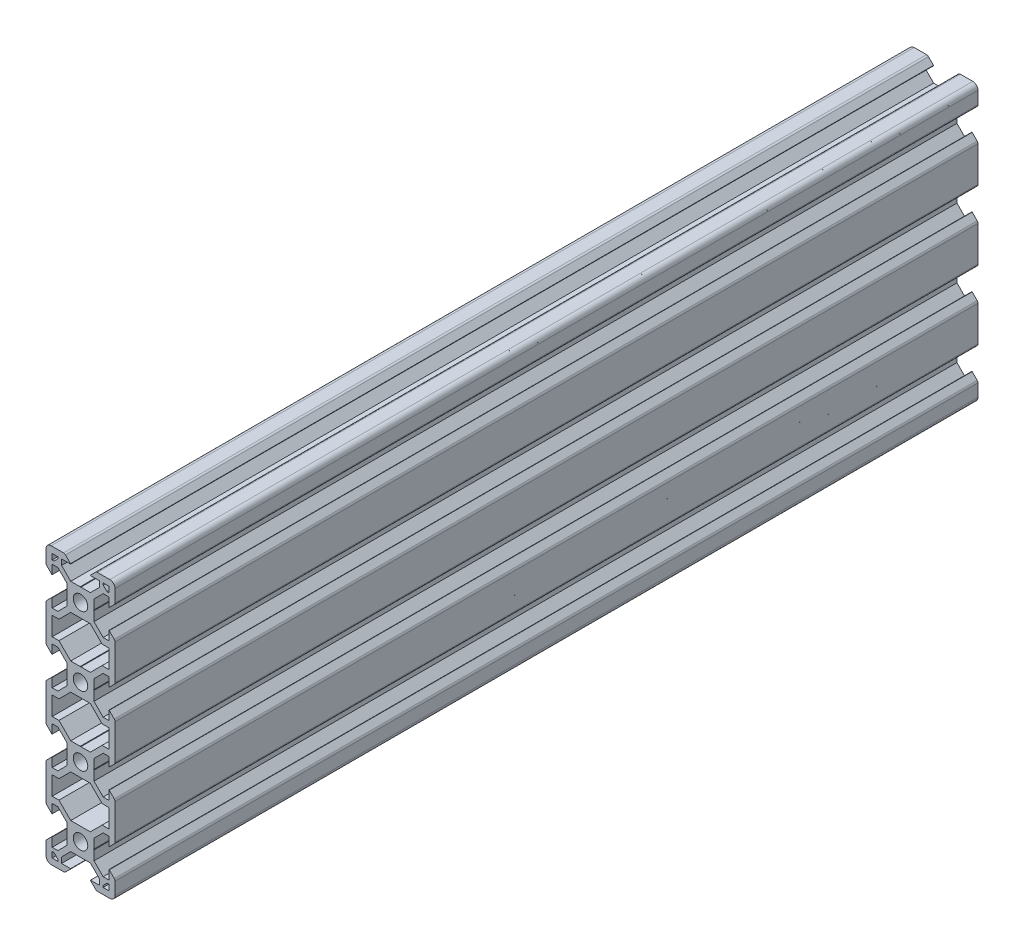
SolidWorks part; units mm, degrees
ref_plane "Front Plane" through (0, 0, 0) normal (0, 0, 1) x (1, 0, 0)
ref_plane "Top Plane" through (0, 0, 0) normal (0, 1, 0) x (1, 0, 0)
ref_plane "Right Plane" through (0, 0, 0) normal (1, 0, 0) x (0, 0, -1)
sketch "Sketch2" plane through (0, 0, 0) normal (0, 0, 1) x (1, 0, 0)
  line L0 (-8.2, 2.8875) -> (-8.2, 5.4975)
  line L3 (-4.9072, 9.9975) -> (-8.5, 9.9975)
  line L4 (-10, 4.9047) -> (-10, 8.4975)
  line L5 (-2.1, 0) -> (-3.8, 0) construction
  line L6 (0, 3.8) -> (0, 2.1) construction
  line L7 (-0.1, 3.9) -> (-2.8404, 3.9)
  line L8 (-3.9, 0.1) -> (-3.9, 2.8383)
  line L9 (-2.89, 8.1975) -> (-5.5, 8.1975)
  line L10 (-6.57, 8.1975) -> (-6.57, 7.6575)
  line L11 (-8.2, 6.5675) -> (-7.66, 6.5675)
  line L12 (-5.5, 8.1975) -> (-5.5, 6.5588)
  line L13 (-6.56, 5.4975) -> (-8.2, 5.4975)
  line L14 (-8.2, 8.1975) -> (-1.4852, 1.4847) construction
  line L15 (-6.56, 5.4975) -> (-3.9, 2.8383)
  line L16 (-5.5, 6.5588) -> (-2.8404, 3.9)
  line L17 (-7.66, 6.5675) -> (-6.57, 7.6575)
  line L18 (-8.7302, 7.6671) -> (-0.5302, -0.5304) construction
  line L19 (-7.6698, 8.7279) -> (0.5302, 0.5304) construction
  line L20 (-8.2, 8.1975) -> (0, 0) construction
  line L21 (-8.2, 6.5675) -> (-8.2, 8.1975)
  line L22 (-8.2, -0.0025) -> (-8.2, 8.1975) construction
  line L23 (-6.57, 8.1975) -> (-8.2, 8.1975)
  line L24 (0, 8.1975) -> (-8.2, 8.1975) construction
  line L25 (-10, -0.0025) -> (-10, 9.9975) construction
  line L26 (0, 9.9975) -> (-10, 9.9975) construction
  line L27 (-2.89, 8.3075) -> (-2.89, 8.1975)
  line L29 (-8.31, 2.8875) -> (-8.2, 2.8875)
  line L30 (-4.3486, 9.7661) -> (-2.89, 8.3075)
  line L31 (-8.31, 2.8875) -> (-9.7686, 4.3461)
  line L34 (-0.1, 3.9) -> (0, 3.8)
  line L35 (-3.9, 0.1) -> (-3.8, 0)
  line L36 (-10, -20) -> (0, -20) construction
  line L37 (0, 0) -> (0, -20) construction
  line L38 (0, -3.9) -> (-2.8404, -3.9)
  line L39 (-3.8, 0) -> (-3.9, -0.1)
  line L40 (-3.9, -0.1) -> (-3.9, -2.84)
  line L41 (-2.8404, -3.9) -> (-6.25, -7.3096)
  line L42 (-3.9, -2.84) -> (-6.56, -5.5)
  line L43 (-8.21, -2.89) -> (-8.21, -5.5)
  line L44 (-6.56, 5.4975) -> (-6.56, -5.5) construction
  line L45 (-6.56, -5.5) -> (-8.21, -5.5)
  line L46 (-6.25, -7.3096) -> (-6.25, -12.7) construction
  line L47 (-6.25, -7.3096) -> (-8.21, -7.3096)
  line L48 (-8.21, -2.89) -> (-8.31, -2.89)
  line L49 (-8.31, -2.89) -> (-9.7657, -4.3457)
  line L51 (-8.21, -7.3096) -> (-8.21, -12.7)
  line L52 (-0.1, -16.1) -> (-2.85, -16.1)
  line L53 (-3.9, -17.16) -> (-3.9, -19.9)
  line L54 (-6.25, -12.7) -> (-2.85, -16.1)
  line L58 (-3.9, -17.16) -> (-6.56, -14.5)
  line L60 (-8.21, -17.11) -> (-8.31, -17.11)
  line L61 (-10, -4.9114) -> (-10, -15.0886)
  line L62 (-9.7657, -15.6543) -> (-8.31, -17.11)
  line L63 (-0.1, -16.1) -> (0, -16.2)
  line L64 (-3.9, -19.9) -> (-3.8, -20)
  line L65 (-8.21, -14.5) -> (-6.56, -14.5)
  line L66 (-8.21, -12.7) -> (-6.25, -12.7)
  line L67 (-10, -30.01) -> (0, -30.01) construction
  line L68 (-8.21, -14.5) -> (-8.21, -17.11)
  line L69 (-3.9, -20.1) -> (-3.8, -20)
  line L71 (-10, -20) -> (0, -20) construction
  line L72 (-8.21, -30.01) -> (-8.21, -27.31)
  line L73 (-10, -30.01) -> (-10, -24.9101)
  line L74 (-8.21, -25.4987) -> (-8.21, -22.8887)
  line L76 (-8.21, -27.31) -> (-6.25, -27.31)
  line L77 (-8.21, -25.4987) -> (-6.56, -25.4987)
  line L85 (-0.1, -23.9) -> (0, -23.8)
  line L95 (-9.7657, -24.3444) -> (-8.31, -22.8887)
  line L96 (-8.21, -22.8887) -> (-8.31, -22.8887)
  line L97 (-3.9, -22.8387) -> (-6.56, -25.4987)
  line L98 (-6.25, -27.31) -> (-2.84, -23.9)
  line L99 (-3.9, -22.8387) -> (-3.9, -20.1)
  line L100 (-0.1, -23.9) -> (-2.84, -23.9)
  arc A1 (-10, 8.4975) -> (-8.5, 9.9975) centre (-8.5, 8.4975) cw
  arc A2 (-9.7686, 4.3461) -> (-10, 4.9047) centre (-9.21, 4.9047) cw
  arc A3 (-4.3486, 9.7661) -> (-4.9072, 9.9975) centre (-4.9072, 9.2075) ccw
  arc A5 (0, 2.1) -> (0, -2.1) centre (0, 0) ccw
  arc A6 (-9.7657, -15.6543) -> (-10, -15.0886) centre (-9.2, -15.0886) cw
  arc A7 (-9.7657, -4.3457) -> (-10, -4.9114) centre (-9.2, -4.9114) ccw
  arc A8 (0, -17.9) -> (0, -22.1) centre (0, -20) ccw
  arc A10 (-9.7657, -24.3444) -> (-10, -24.9101) centre (-9.2, -24.9101) ccw
  point P29 (-10, 9.9975)
  point P39 (-10, 4.5775)
  point P42 (-4.58, 9.9975)
  point P76 (-10, -15.42)
  point P79 (-10, -4.58)
  dimension "D15" = 1.5
  dimension "D22" = 0.79
  dimension "D30" = 2.1
  dimension "D31" = 2.1
  dimension "D51" = 0.8
  dimension "D52" = 2.61
  dimension "D64" = 1.65
  dimension "D53" = 0.8
  dimension "D55" = 3.9
  dimension "D4" = 1.8
  dimension "D5" = 3.43
  dimension "D6" = 3.43
  dimension "D7" = 0.54
  dimension "D8" = 0.54
  dimension "D9" = 1.07
  dimension "D10" = 1.07
  dimension "D11" = 3.9
  dimension "D12" = 3.9
  dimension "D16" = 7.11
  dimension "D17" = 0.11
  dimension "D18" = 1.69
  dimension "D19" = 0.11
  dimension "D20" = 7.11
  dimension "D21" = 1.69
  dimension "D23" = 10
  dimension "D24" = 0.1
  dimension "D25" = 45
  dimension "D26" = 0.1
  dimension "D27" = 45
  dimension "D28" = 1.64
  dimension "D29" = 20
  dimension "D32" = 3.9
  dimension "D33" = 45
  dimension "D34" = 2.74
  dimension "D35" = 45
  dimension "D36" = 1.96
  dimension "D37" = 2.61
  dimension "D38" = 90
  dimension "D39" = 2.61
  dimension "D40" = 3.9
  dimension "D41" = 3.9
  dimension "D42" = 135
  dimension "D44" = 45
  dimension "D45" = 1.8
  dimension "D46" = 0.1
  dimension "D47" = 0.1
  dimension "D48" = 45
  dimension "D49" = 0.1
  dimension "D50" = 45
  dimension "D43" = 5.5
  dimension "D54" = 3.9
  dimension "D56" = 45
  dimension "D57" = 2.7
  dimension "D59" = 45
  dimension "D60" = 0.1
  dimension "D61" = 0.1
  dimension "D62" = 45
  dimension "D63" = 2.84
  dimension "D65" = 1.96
  dimension "D66" = 45
  dimension "D67" = 1.5
  dimension "D13" = 0.75
  dimension "D14" = 0.75
sketch "Sketch3" plane through (0, 0, 0) normal (0, 0, 1) x (1, 0, 0)
  line L0 (-0.1, 3.9) -> (0, 3.8) construction
  line L1 (-0.1, 3.9) -> (-2.8404, 3.9) construction
  line L2 (-5.5, 6.5588) -> (-2.8404, 3.9) construction
  line L3 (-5.5, 8.1975) -> (-5.5, 6.5588) construction
  line L4 (-2.89, 8.1975) -> (-5.5, 8.1975) construction
  line L5 (-7.66, 6.5675) -> (-6.57, 7.6575)
  line L6 (-6.57, 7.6575) -> (-6.57, 8.1975)
  line L7 (-6.57, 8.1975) -> (-8.2, 8.1975)
  line L8 (-8.2, 8.1975) -> (-8.2, 6.5675)
  line L9 (-8.2, 6.5675) -> (-7.66, 6.5675)
  line L10 (-7.66, 6.5675) -> (-6.57, 7.6575)
  line L11 (-6.57, 7.6575) -> (-6.57, 8.1975)
  line L12 (-6.57, 8.1975) -> (-8.2, 8.1975)
  line L13 (-8.2, 8.1975) -> (-8.2, 6.5675)
  line L14 (-8.2, 6.5675) -> (-7.66, 6.5675)
  line L15 (-2.89, 8.3075) -> (-2.89, 8.1975) construction
  line L16 (-4.3486, 9.7661) -> (-2.89, 8.3075) construction
  line L17 (-4.9072, 9.9975) -> (-8.5, 9.9975) construction
  line L18 (-10, 4.9047) -> (-10, 8.4975) construction
  line L19 (-8.31, 2.8875) -> (-9.7686, 4.3461) construction
  line L20 (-8.31, 2.8875) -> (-8.2, 2.8875) construction
  line L21 (-8.2, 2.8875) -> (-8.2, 5.4975) construction
  line L22 (-6.56, 5.4975) -> (-8.2, 5.4975) construction
  line L23 (-6.56, 5.4975) -> (-3.9, 2.8383) construction
  line L24 (-3.9, 0.1) -> (-3.9, 2.8383) construction
  line L25 (-3.9, 0.1) -> (-3.8, 0) construction
  line L26 (-3.8, 0) -> (-3.9, -0.1) construction
  line L27 (-3.9, -0.1) -> (-3.9, -2.84) construction
  line L28 (-3.9, -2.84) -> (-6.56, -5.5) construction
  line L29 (-6.56, -5.5) -> (-8.21, -5.5) construction
  line L30 (-8.21, -2.89) -> (-8.21, -5.5) construction
  line L31 (-8.21, -2.89) -> (-8.31, -2.89) construction
  line L32 (-8.31, -2.89) -> (-9.7657, -4.3457) construction
  line L33 (-10, -4.9114) -> (-10, -15.0886) construction
  line L34 (-9.7657, -15.6543) -> (-8.31, -17.11) construction
  line L35 (-8.21, -17.11) -> (-8.31, -17.11) construction
  line L36 (-8.21, -14.5) -> (-8.21, -17.11) construction
  line L37 (-8.21, -14.5) -> (-6.56, -14.5) construction
  line L38 (-3.9, -17.16) -> (-6.56, -14.5) construction
  line L39 (-3.9, -17.16) -> (-3.9, -19.9) construction
  line L40 (-3.9, -19.9) -> (-3.8, -20) construction
  line L41 (-3.9, -20.1) -> (-3.8, -20) construction
  line L42 (-3.9, -22.8387) -> (-3.9, -20.1) construction
  line L43 (-3.9, -22.8387) -> (-6.56, -25.4987) construction
  line L44 (-8.21, -25.4987) -> (-6.56, -25.4987) construction
  line L45 (-8.21, -25.4987) -> (-8.21, -22.8887) construction
  line L46 (-8.21, -22.8887) -> (-8.31, -22.8887) construction
  line L47 (-9.7657, -24.3444) -> (-8.31, -22.8887) construction
  line L48 (-10, -30.01) -> (-10, -24.9101) construction
  line L49 (0, -3.9) -> (-2.8404, -3.9) construction
  line L50 (-2.8404, -3.9) -> (-6.25, -7.3096) construction
  line L51 (-6.25, -7.3096) -> (-8.21, -7.3096) construction
  line L52 (-8.21, -7.3096) -> (-8.21, -12.7) construction
  line L53 (-8.21, -12.7) -> (-6.25, -12.7) construction
  line L54 (-6.25, -12.7) -> (-2.85, -16.1) construction
  line L55 (-0.1, -16.1) -> (-2.85, -16.1) construction
  line L56 (-0.1, -16.1) -> (0, -16.2) construction
  line L57 (-0.1, -23.9) -> (0, -23.8) construction
  line L58 (-0.1, -23.9) -> (-2.84, -23.9) construction
  line L59 (-6.25, -27.31) -> (-2.84, -23.9) construction
  line L60 (-8.21, -27.31) -> (-6.25, -27.31) construction
  line L61 (-8.21, -30.01) -> (-8.21, -27.31) construction
  line L62 (-0.1, 3.9) -> (0, 3.8)
  line L63 (-0.1, 3.9) -> (-2.8404, 3.9)
  line L64 (-5.5, 6.5588) -> (-2.8404, 3.9)
  line L65 (-5.5, 8.1975) -> (-5.5, 6.5588)
  line L66 (-2.89, 8.1975) -> (-5.5, 8.1975)
  line L67 (-2.89, 8.3075) -> (-2.89, 8.1975)
  line L68 (-4.3486, 9.7661) -> (-2.89, 8.3075)
  line L69 (-4.9072, 9.9975) -> (-8.5, 9.9975)
  line L70 (-10, 4.9047) -> (-10, 8.4975)
  line L71 (-8.31, 2.8875) -> (-9.7686, 4.3461)
  line L72 (-8.31, 2.8875) -> (-8.2, 2.8875)
  line L73 (-8.2, 2.8875) -> (-8.2, 5.4975)
  line L74 (-6.56, 5.4975) -> (-8.2, 5.4975)
  line L75 (-6.56, 5.4975) -> (-3.9, 2.8383)
  line L76 (-3.9, 0.1) -> (-3.9, 2.8383)
  line L77 (-3.9, 0.1) -> (-3.8, 0)
  line L78 (-3.8, 0) -> (-3.9, -0.1)
  line L79 (-3.9, -0.1) -> (-3.9, -2.84)
  line L80 (-3.9, -2.84) -> (-6.56, -5.5)
  line L81 (-6.56, -5.5) -> (-8.21, -5.5)
  line L82 (-8.21, -2.89) -> (-8.21, -5.5)
  line L83 (-8.21, -2.89) -> (-8.31, -2.89)
  line L84 (-8.31, -2.89) -> (-9.7657, -4.3457)
  line L85 (-10, -4.9114) -> (-10, -15.0886)
  line L86 (-9.7657, -15.6543) -> (-8.31, -17.11)
  line L87 (-8.21, -17.11) -> (-8.31, -17.11)
  line L88 (-8.21, -14.5) -> (-8.21, -17.11)
  line L89 (-8.21, -14.5) -> (-6.56, -14.5)
  line L90 (-3.9, -17.16) -> (-6.56, -14.5)
  line L91 (-3.9, -17.16) -> (-3.9, -19.9)
  line L92 (-3.9, -19.9) -> (-3.8, -20)
  line L93 (-3.9, -20.1) -> (-3.8, -20)
  line L94 (-3.9, -22.8387) -> (-3.9, -20.1)
  line L95 (-3.9, -22.8387) -> (-6.56, -25.4987)
  line L96 (-8.21, -25.4987) -> (-6.56, -25.4987)
  line L97 (-8.21, -25.4987) -> (-8.21, -22.8887)
  line L98 (-8.21, -22.8887) -> (-8.31, -22.8887)
  line L99 (-9.7657, -24.3444) -> (-8.31, -22.8887)
  line L100 (-10, -35.1099) -> (-10, -24.9101)
  line L101 (2.8404, -3.9) -> (-2.8404, -3.9)
  line L102 (-2.8404, -3.9) -> (-6.25, -7.3096)
  line L103 (-6.25, -7.3096) -> (-8.21, -7.3096)
  line L104 (-8.21, -7.3096) -> (-8.21, -12.7)
  line L105 (-8.21, -12.7) -> (-6.25, -12.7)
  line L106 (-6.25, -12.7) -> (-2.85, -16.1)
  line L107 (-0.1, -16.1) -> (-2.85, -16.1)
  line L108 (-0.1, -16.1) -> (0, -16.2)
  line L109 (-0.1, -23.9) -> (0, -23.8)
  line L110 (-0.1, -23.9) -> (-2.84, -23.9)
  line L111 (-6.25, -27.31) -> (-2.84, -23.9)
  line L112 (-8.21, -27.31) -> (-6.25, -27.31)
  line L113 (-8.21, -32.71) -> (-8.21, -27.31)
  line L114 (0, 0) -> (0, -20) construction
  line L115 (-10, -30.01) -> (0, -30.01) construction
  line L116 (0, 0) -> (0, -20) construction
  line L117 (-10, -30.01) -> (10, -30.01) construction
  line L118 (8.21, -32.71) -> (8.21, -27.31)
  line L119 (8.21, -27.31) -> (6.25, -27.31)
  line L120 (6.25, -27.31) -> (2.84, -23.9)
  line L121 (0.1, -23.9) -> (2.84, -23.9)
  line L122 (0.1, -23.9) -> (0, -23.8)
  line L123 (0.1, -16.1) -> (0, -16.2)
  line L124 (0.1, -16.1) -> (2.85, -16.1)
  line L125 (6.25, -12.7) -> (2.85, -16.1)
  line L126 (8.21, -12.7) -> (6.25, -12.7)
  line L127 (8.21, -7.3096) -> (8.21, -12.7)
  line L128 (6.25, -7.3096) -> (8.21, -7.3096)
  line L129 (2.8404, -3.9) -> (6.25, -7.3096)
  line L130 (10, -35.1099) -> (10, -24.9101)
  line L131 (9.7657, -24.3444) -> (8.31, -22.8887)
  line L132 (8.21, -22.8887) -> (8.31, -22.8887)
  line L133 (8.21, -25.4987) -> (8.21, -22.8887)
  line L134 (8.21, -25.4987) -> (6.56, -25.4987)
  line L135 (3.9, -22.8387) -> (6.56, -25.4987)
  line L136 (3.9, -22.8387) -> (3.9, -20.1)
  line L137 (3.9, -20.1) -> (3.8, -20)
  line L138 (3.9, -19.9) -> (3.8, -20)
  line L139 (3.9, -17.16) -> (3.9, -19.9)
  line L140 (3.9, -17.16) -> (6.56, -14.5)
  line L141 (8.21, -14.5) -> (6.56, -14.5)
  line L142 (8.21, -14.5) -> (8.21, -17.11)
  line L143 (8.21, -17.11) -> (8.31, -17.11)
  line L144 (9.7657, -15.6543) -> (8.31, -17.11)
  line L145 (10, -4.9114) -> (10, -15.0886)
  line L146 (8.31, -2.89) -> (9.7657, -4.3457)
  line L147 (8.21, -2.89) -> (8.31, -2.89)
  line L148 (8.21, -2.89) -> (8.21, -5.5)
  line L149 (6.56, -5.5) -> (8.21, -5.5)
  line L150 (3.9, -2.84) -> (6.56, -5.5)
  line L151 (3.9, -0.1) -> (3.9, -2.84)
  line L152 (3.8, 0) -> (3.9, -0.1)
  line L153 (3.9, 0.1) -> (3.8, 0)
  line L154 (3.9, 0.1) -> (3.9, 2.8383)
  line L155 (6.56, 5.4975) -> (3.9, 2.8383)
  line L156 (6.56, 5.4975) -> (8.2, 5.4975)
  line L157 (8.2, 2.8875) -> (8.2, 5.4975)
  line L158 (8.31, 2.8875) -> (8.2, 2.8875)
  line L159 (8.31, 2.8875) -> (9.7686, 4.3461)
  line L160 (10, 4.9047) -> (10, 8.4975)
  line L161 (4.9072, 9.9975) -> (8.5, 9.9975)
  line L162 (4.3486, 9.7661) -> (2.89, 8.3075)
  line L163 (2.89, 8.3075) -> (2.89, 8.1975)
  line L164 (2.89, 8.1975) -> (5.5, 8.1975)
  line L165 (5.5, 8.1975) -> (5.5, 6.5588)
  line L166 (5.5, 6.5588) -> (2.8404, 3.9)
  line L167 (0.1, 3.9) -> (2.8404, 3.9)
  line L168 (0.1, 3.9) -> (0, 3.8)
  line L169 (8.2, 6.5675) -> (7.66, 6.5675)
  line L170 (8.2, 8.1975) -> (8.2, 6.5675)
  line L171 (6.57, 8.1975) -> (8.2, 8.1975)
  line L172 (6.57, 7.6575) -> (6.57, 8.1975)
  line L173 (7.66, 6.5675) -> (6.57, 7.6575)
  line L174 (0, -60.02) -> (0, -40.02) construction
  line L175 (7.66, -66.5875) -> (6.57, -67.6775)
  line L176 (6.57, -67.6775) -> (6.57, -68.2175)
  line L177 (6.57, -68.2175) -> (8.2, -68.2175)
  line L178 (8.2, -68.2175) -> (8.2, -66.5875)
  line L179 (8.2, -66.5875) -> (7.66, -66.5875)
  line L180 (0.1, -63.92) -> (0, -63.82)
  line L181 (0.1, -63.92) -> (2.8404, -63.92)
  line L182 (5.5, -66.5788) -> (2.8404, -63.92)
  line L183 (5.5, -68.2175) -> (5.5, -66.5788)
  line L184 (2.89, -68.2175) -> (5.5, -68.2175)
  line L185 (2.89, -68.3275) -> (2.89, -68.2175)
  line L186 (4.3486, -69.7861) -> (2.89, -68.3275)
  line L187 (4.9072, -70.0175) -> (8.5, -70.0175)
  line L188 (10, -64.9247) -> (10, -68.5175)
  line L189 (8.31, -62.9075) -> (9.7686, -64.3661)
  line L190 (8.31, -62.9075) -> (8.2, -62.9075)
  line L191 (8.2, -62.9075) -> (8.2, -65.5175)
  line L192 (6.56, -65.5175) -> (8.2, -65.5175)
  line L193 (6.56, -65.5175) -> (3.9, -62.8583)
  line L194 (3.9, -60.12) -> (3.9, -62.8583)
  line L195 (3.9, -60.12) -> (3.8, -60.02)
  line L196 (3.8, -60.02) -> (3.9, -59.92)
  line L197 (3.9, -59.92) -> (3.9, -57.18)
  line L198 (3.9, -57.18) -> (6.56, -54.52)
  line L199 (6.56, -54.52) -> (8.21, -54.52)
  line L200 (8.21, -57.13) -> (8.21, -54.52)
  line L201 (8.21, -57.13) -> (8.31, -57.13)
  line L202 (8.31, -57.13) -> (9.7657, -55.6743)
  line L203 (10, -55.1086) -> (10, -44.9314)
  line L204 (9.7657, -44.3657) -> (8.31, -42.91)
  line L205 (8.21, -42.91) -> (8.31, -42.91)
  line L206 (8.21, -45.52) -> (8.21, -42.91)
  line L207 (8.21, -45.52) -> (6.56, -45.52)
  line L208 (3.9, -42.86) -> (6.56, -45.52)
  line L209 (3.9, -42.86) -> (3.9, -40.12)
  line L210 (3.9, -40.12) -> (3.8, -40.02)
  line L211 (3.9, -39.92) -> (3.8, -40.02)
  line L212 (3.9, -37.1813) -> (3.9, -39.92)
  line L213 (3.9, -37.1813) -> (6.56, -34.5213)
  line L214 (8.21, -34.5213) -> (6.56, -34.5213)
  line L215 (8.21, -34.5213) -> (8.21, -37.1313)
  line L216 (8.21, -37.1313) -> (8.31, -37.1313)
  line L217 (9.7657, -35.6756) -> (8.31, -37.1313)
  line L218 (2.8404, -56.12) -> (6.25, -52.7104)
  line L219 (6.25, -52.7104) -> (8.21, -52.7104)
  line L220 (8.21, -52.7104) -> (8.21, -47.32)
  line L221 (8.21, -47.32) -> (6.25, -47.32)
  line L222 (6.25, -47.32) -> (2.85, -43.92)
  line L223 (0.1, -43.92) -> (2.85, -43.92)
  line L224 (0.1, -43.92) -> (0, -43.82)
  line L225 (0.1, -36.12) -> (0, -36.22)
  line L226 (0.1, -36.12) -> (2.84, -36.12)
  line L227 (6.25, -32.71) -> (2.84, -36.12)
  line L228 (8.21, -32.71) -> (6.25, -32.71)
  line L229 (-8.21, -32.71) -> (-6.25, -32.71)
  line L230 (-6.25, -32.71) -> (-2.84, -36.12)
  line L231 (-0.1, -36.12) -> (-2.84, -36.12)
  line L232 (-0.1, -36.12) -> (0, -36.22)
  line L233 (-0.1, -43.92) -> (0, -43.82)
  line L234 (-0.1, -43.92) -> (-2.85, -43.92)
  line L235 (-6.25, -47.32) -> (-2.85, -43.92)
  line L236 (-8.21, -47.32) -> (-6.25, -47.32)
  line L237 (-8.21, -52.7104) -> (-8.21, -47.32)
  line L238 (-6.25, -52.7104) -> (-8.21, -52.7104)
  line L239 (-2.8404, -56.12) -> (-6.25, -52.7104)
  line L240 (2.8404, -56.12) -> (-2.8404, -56.12)
  line L241 (-9.7657, -35.6756) -> (-8.31, -37.1313)
  line L242 (-8.21, -37.1313) -> (-8.31, -37.1313)
  line L243 (-8.21, -34.5213) -> (-8.21, -37.1313)
  line L244 (-8.21, -34.5213) -> (-6.56, -34.5213)
  line L245 (-3.9, -37.1813) -> (-6.56, -34.5213)
  line L246 (-3.9, -37.1813) -> (-3.9, -39.92)
  line L247 (-3.9, -39.92) -> (-3.8, -40.02)
  line L248 (-3.9, -40.12) -> (-3.8, -40.02)
  line L249 (-3.9, -42.86) -> (-3.9, -40.12)
  line L250 (-3.9, -42.86) -> (-6.56, -45.52)
  line L251 (-8.21, -45.52) -> (-6.56, -45.52)
  line L252 (-8.21, -45.52) -> (-8.21, -42.91)
  line L253 (-8.21, -42.91) -> (-8.31, -42.91)
  line L254 (-9.7657, -44.3657) -> (-8.31, -42.91)
  line L255 (-10, -55.1086) -> (-10, -44.9314)
  line L256 (-8.31, -57.13) -> (-9.7657, -55.6743)
  line L257 (-8.21, -57.13) -> (-8.31, -57.13)
  line L258 (-8.21, -57.13) -> (-8.21, -54.52)
  line L259 (-6.56, -54.52) -> (-8.21, -54.52)
  line L260 (-3.9, -57.18) -> (-6.56, -54.52)
  line L261 (-3.9, -59.92) -> (-3.9, -57.18)
  line L262 (-3.8, -60.02) -> (-3.9, -59.92)
  line L263 (-3.9, -60.12) -> (-3.8, -60.02)
  line L264 (-3.9, -60.12) -> (-3.9, -62.8583)
  line L265 (-6.56, -65.5175) -> (-3.9, -62.8583)
  line L266 (-6.56, -65.5175) -> (-8.2, -65.5175)
  line L267 (-8.2, -62.9075) -> (-8.2, -65.5175)
  line L268 (-8.31, -62.9075) -> (-8.2, -62.9075)
  line L269 (-8.31, -62.9075) -> (-9.7686, -64.3661)
  line L270 (-10, -64.9247) -> (-10, -68.5175)
  line L271 (-4.9072, -70.0175) -> (-8.5, -70.0175)
  line L272 (-4.3486, -69.7861) -> (-2.89, -68.3275)
  line L273 (-2.89, -68.3275) -> (-2.89, -68.2175)
  line L274 (-2.89, -68.2175) -> (-5.5, -68.2175)
  line L275 (-5.5, -68.2175) -> (-5.5, -66.5788)
  line L276 (-5.5, -66.5788) -> (-2.8404, -63.92)
  line L277 (-0.1, -63.92) -> (-2.8404, -63.92)
  line L278 (-0.1, -63.92) -> (0, -63.82)
  line L279 (-8.2, -66.5875) -> (-7.66, -66.5875)
  line L280 (-8.2, -68.2175) -> (-8.2, -66.5875)
  line L281 (-6.57, -68.2175) -> (-8.2, -68.2175)
  line L282 (-6.57, -67.6775) -> (-6.57, -68.2175)
  line L283 (-7.66, -66.5875) -> (-6.57, -67.6775)
  arc A0 (0, 2.1) -> (0, -2.1) centre (0, 0) ccw construction
  arc A1 (0, -17.9) -> (0, -22.1) centre (0, -20) ccw construction
  arc A2 (-4.3486, 9.7661) -> (-4.9072, 9.9975) centre (-4.9072, 9.2075) ccw construction
  arc A3 (-8.5, 9.9975) -> (-10, 8.4975) centre (-8.5, 8.4975) ccw construction
  arc A4 (-10, 4.9047) -> (-9.7686, 4.3461) centre (-9.21, 4.9047) ccw construction
  arc A5 (-9.7657, -4.3457) -> (-10, -4.9114) centre (-9.2, -4.9114) ccw construction
  arc A6 (-10, -15.0886) -> (-9.7657, -15.6543) centre (-9.2, -15.0886) ccw construction
  arc A7 (-9.7657, -24.3444) -> (-10, -24.9101) centre (-9.2, -24.9101) ccw construction
  circle A8 centre (0, 0) radius 2.1
  circle A9 centre (0, -20) radius 2.1
  arc A10 (-4.3486, 9.7661) -> (-4.9072, 9.9975) centre (-4.9072, 9.2075) ccw
  arc A11 (-8.5, 9.9975) -> (-10, 8.4975) centre (-8.5, 8.4975) ccw
  arc A12 (-10, 4.9047) -> (-9.7686, 4.3461) centre (-9.21, 4.9047) ccw
  arc A13 (-9.7657, -4.3457) -> (-10, -4.9114) centre (-9.2, -4.9114) ccw
  arc A14 (-10, -15.0886) -> (-9.7657, -15.6543) centre (-9.2, -15.0886) ccw
  arc A15 (-9.7657, -24.3444) -> (-10, -24.9101) centre (-9.2, -24.9101) ccw
  arc A16 (9.7657, -24.3444) -> (10, -24.9101) centre (9.2, -24.9101) cw
  arc A17 (10, -15.0886) -> (9.7657, -15.6543) centre (9.2, -15.0886) cw
  arc A18 (9.7657, -4.3457) -> (10, -4.9114) centre (9.2, -4.9114) cw
  arc A19 (10, 4.9047) -> (9.7686, 4.3461) centre (9.21, 4.9047) cw
  arc A20 (8.5, 9.9975) -> (10, 8.4975) centre (8.5, 8.4975) cw
  arc A21 (4.3486, 9.7661) -> (4.9072, 9.9975) centre (4.9072, 9.2075) cw
  arc A22 (4.3486, -69.7861) -> (4.9072, -70.0175) centre (4.9072, -69.2275) ccw
  arc A23 (8.5, -70.0175) -> (10, -68.5175) centre (8.5, -68.5175) ccw
  arc A24 (10, -64.9247) -> (9.7686, -64.3661) centre (9.21, -64.9247) ccw
  arc A25 (9.7657, -55.6743) -> (10, -55.1086) centre (9.2, -55.1086) ccw
  arc A26 (10, -44.9314) -> (9.7657, -44.3657) centre (9.2, -44.9314) ccw
  arc A27 (9.7657, -35.6756) -> (10, -35.1099) centre (9.2, -35.1099) ccw
  arc A28 (-9.7657, -35.6756) -> (-10, -35.1099) centre (-9.2, -35.1099) cw
  arc A29 (-10, -44.9314) -> (-9.7657, -44.3657) centre (-9.2, -44.9314) cw
  arc A30 (-9.7657, -55.6743) -> (-10, -55.1086) centre (-9.2, -55.1086) cw
  arc A31 (-10, -64.9247) -> (-9.7686, -64.3661) centre (-9.21, -64.9247) cw
  arc A32 (-8.5, -70.0175) -> (-10, -68.5175) centre (-8.5, -68.5175) cw
  arc A33 (-4.3486, -69.7861) -> (-4.9072, -70.0175) centre (-4.9072, -69.2275) cw
  circle A34 centre (0, -40.02) radius 2.1
  circle A35 centre (0, -60.02) radius 2.1
  point P240 (8.21, -30.01)
  point P288 (-0.1, 9.9975)
  point P289 (0, -70.0175)
  point P290 (-10, -60.02)
  point P291 (10, -60.02)
  point P292 (10, -40.02)
  point P293 (-10, -40.02)
  point P294 (-10, -20)
  point P295 (10, -20)
  point P296 (10, 0)
  point P297 (-10, 0)
  point P298 (-45.6583, 8.4975)
  dimension "D2" = 20
  dimension "D3" = 10.01
  dimension "D1" = 0
extrude "Boss-Extrude1" add sketch "Sketch3" against normal blind 250
